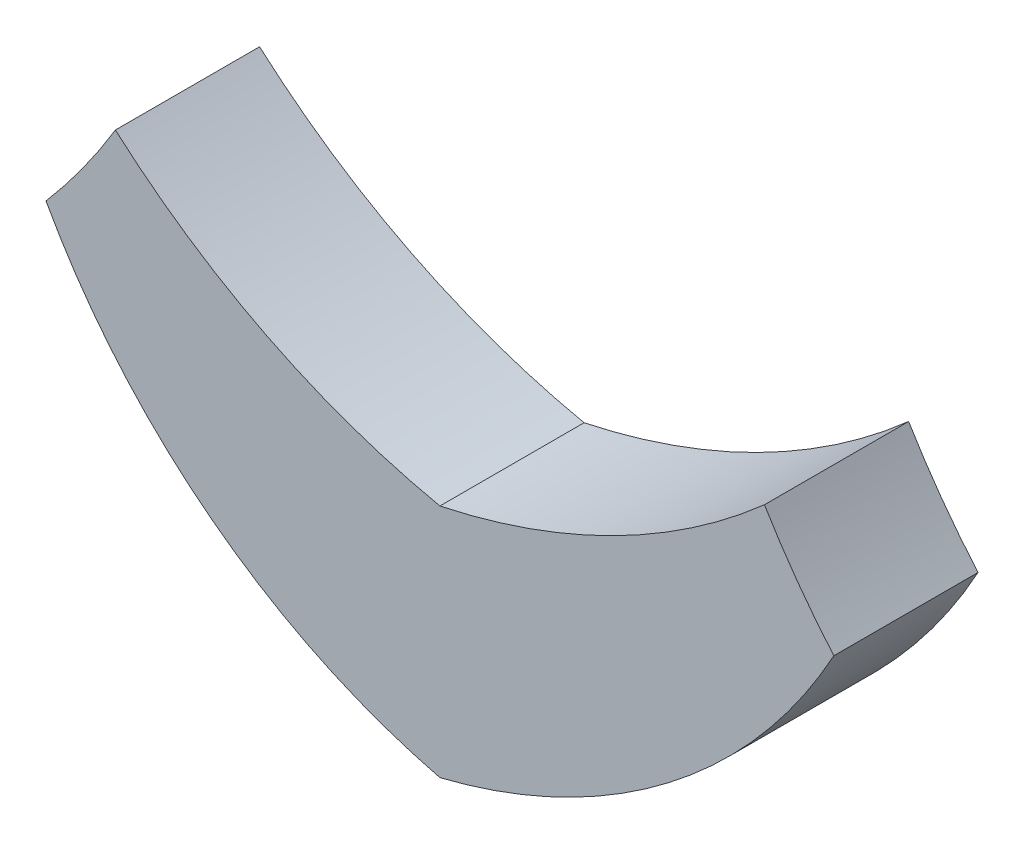
SolidWorks part; units mm, degrees
ref_plane "Front Plane" through (0, 0, 0) normal (0, 0, 1) x (1, 0, 0)
ref_plane "Top Plane" through (0, 0, 0) normal (0, 1, 0) x (1, 0, 0)
ref_plane "Right Plane" through (0, 0, 0) normal (1, 0, 0) x (0, 0, -1)
sketch "Sketch1" plane through (0, 0, 0) normal (0, 0, 1) x (1, 0, 0)
  arc A0 (-12.9831, 6.1186) -> (-10.5771, 9.4512) centre (-31.7625, 22.2106) ccw
  arc A1 (-7.983, 7.4481) -> (-10.5771, 9.4512) centre (5.8016, 27.9812) cw
  arc A2 (-7.983, 7.4481) -> (0.6772, 3.7869) centre (5.8016, 27.9812) ccw
  arc A3 (9.3375, 7.4481) -> (0.6772, 3.7869) centre (-4.4471, 27.9812) cw
  arc A4 (9.3375, 7.4481) -> (11.9316, 9.4512) centre (-4.4471, 27.9812) ccw
  arc A5 (14.3376, 6.1186) -> (11.9316, 9.4512) centre (33.117, 22.2106) cw
  arc A6 (9.3375, 0.0272) -> (14.3376, 6.1186) centre (-4.4471, 16.4401) ccw
  arc A7 (9.3375, 0.0272) -> (0.6772, -4.3719) centre (-4.4471, 16.4401) cw
  arc A8 (-7.983, 0.0272) -> (0.6772, -4.3719) centre (5.8016, 16.4401) ccw
  arc A9 (-7.983, 0.0272) -> (-12.9831, 6.1186) centre (5.8016, 16.4401) cw
extrude "Boss-Extrude1" add sketch "Sketch1" along normal blind 5
